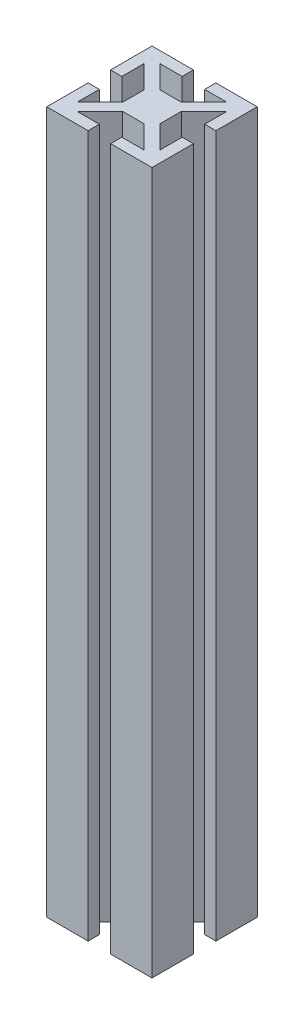
SolidWorks part; units mm, degrees
ref_plane "Front Plane" through (0, 0, 0) normal (0, 0, 1) x (1, 0, 0)
ref_plane "Top Plane" through (0, 0, 0) normal (0, 1, 0) x (1, 0, 0)
ref_plane "Right Plane" through (0, 0, 0) normal (1, 0, 0) x (0, 0, -1)
sketch "Sketch3" plane through (0, 0, 0) normal (0, 0, 1) x (1, 0, 0)
  line L0 (0, 0) -> (0, -254)
  dimension "Length" = 254
sketch "Sketch2" plane through (0, 0, 0) normal (0, 1, 0) x (1, 0, 0)
  line L0 (0, 0) -> (0, 20.2394) construction
  line L1 (0, 0) -> (-20.2394, 0) construction
  line L2 (0, 0) -> (-20.2394, 20.2394) construction
  line L3 (-19.05, 19.05) -> (-4.064, 19.05)
  line L4 (-4.064, 19.05) -> (-4.064, 14.986)
  line L5 (-4.064, 14.986) -> (-12.1123, 14.986)
  line L6 (-12.1123, 14.986) -> (-3.8827, 6.7564)
  line L7 (-3.8827, 6.7564) -> (3.8827, 6.7564)
  line L8 (-19.05, 19.05) -> (-19.05, 4.064)
  line L9 (-19.05, 4.064) -> (-14.986, 4.064)
  line L10 (-14.986, 4.064) -> (-14.986, 12.1123)
  line L11 (-14.986, 12.1123) -> (-6.7564, 3.8827)
  line L12 (-6.7564, 3.8827) -> (-6.7564, -3.8827)
  line L13 (-3.8827, -6.7564) -> (3.8827, -6.7564)
  line L14 (-12.1123, -14.986) -> (-3.8827, -6.7564)
  line L15 (-4.064, -14.986) -> (-12.1123, -14.986)
  line L16 (-4.064, -19.05) -> (-4.064, -14.986)
  line L17 (-19.05, -19.05) -> (-4.064, -19.05)
  line L18 (-19.05, -19.05) -> (-19.05, -4.064)
  line L19 (-19.05, -4.064) -> (-14.986, -4.064)
  line L20 (-14.986, -4.064) -> (-14.986, -12.1123)
  line L21 (-14.986, -12.1123) -> (-6.7564, -3.8827)
  line L22 (12.1123, 14.986) -> (3.8827, 6.7564)
  line L23 (4.064, 14.986) -> (12.1123, 14.986)
  line L24 (4.064, 19.05) -> (4.064, 14.986)
  line L25 (19.05, 19.05) -> (4.064, 19.05)
  line L26 (19.05, 19.05) -> (19.05, 4.064)
  line L27 (19.05, 4.064) -> (14.986, 4.064)
  line L28 (14.986, 4.064) -> (14.986, 12.1123)
  line L29 (14.986, 12.1123) -> (6.7564, 3.8827)
  line L30 (6.7564, 3.8827) -> (6.7564, -3.8827)
  line L31 (14.986, -12.1123) -> (6.7564, -3.8827)
  line L32 (14.986, -4.064) -> (14.986, -12.1123)
  line L33 (19.05, -4.064) -> (14.986, -4.064)
  line L34 (19.05, -19.05) -> (19.05, -4.064)
  line L35 (19.05, -19.05) -> (4.064, -19.05)
  line L36 (4.064, -19.05) -> (4.064, -14.986)
  line L37 (4.064, -14.986) -> (12.1123, -14.986)
  line L38 (12.1123, -14.986) -> (3.8827, -6.7564)
  point P26 (-6.7564, 0)
  point P27 (0, 6.7564)
  point P44 (0, -6.7564)
  dimension "D1" = 38.1
  dimension "D2" = 8.128
  dimension "D3" = 13.5128
  dimension "D4" = 4.064
  dimension "D5" = 4.064
extrude "Boss-Extrude1" add sketch "Sketch2" against normal up to vertex (254 mm away) up to point (0, -254, 0)
